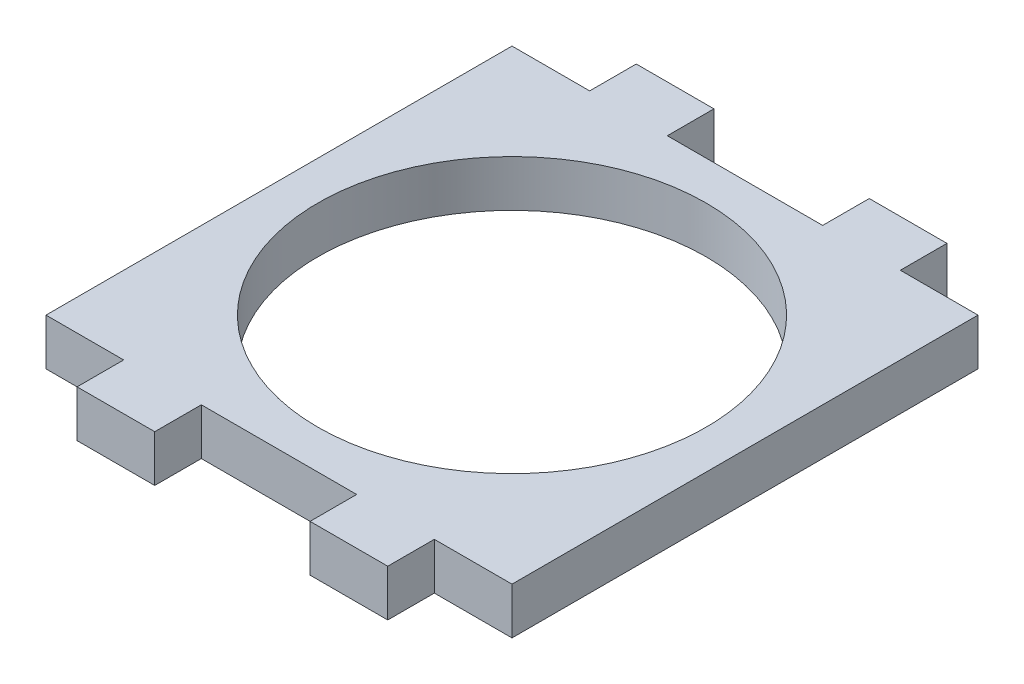
SolidWorks part; units mm, degrees
ref_plane "Front Plane" through (0, 0, 0) normal (0, 0, 1) x (1, 0, 0)
ref_plane "Top Plane" through (0, 0, 0) normal (0, 1, 0) x (1, 0, 0)
ref_plane "Right Plane" through (0, 0, 0) normal (1, 0, 0) x (0, 0, -1)
sketch "Sketch1" plane through (0, 0, 0) normal (0, 1, 0) x (1, 0, 0)
  line L0 (2.2355, 32.0745) -> (0, 30) construction
  line L1 (-30, 30) -> (30, 30)
  line L2 (-30, 30) -> (-30, -30)
  line L3 (-30, -30) -> (30, -30)
  line L4 (30, 30) -> (30, -30)
  line L5 (-30, 30) -> (30, -30) construction
  line L6 (-30, -30) -> (30, 30) construction
  line L7 (0, 30) -> (0, -30) construction
  line L8 (-30, 0) -> (30, 0) construction
  line L9 (10, -30) -> (10, -36)
  line L10 (-20, -30) -> (-10, -30)
  line L11 (-20, -30) -> (-20, -36)
  line L12 (-20, -36) -> (-10, -36)
  line L13 (-10, -30) -> (-10, -36)
  line L14 (20, -36) -> (10, -36)
  line L15 (20, -30) -> (20, -36)
  line L16 (20, -30) -> (10, -30)
  line L25 (-10, 30) -> (-10, 36)
  line L26 (20, 30) -> (10, 30)
  line L27 (20, 30) -> (20, 36)
  line L28 (20, 36) -> (10, 36)
  line L29 (10, 30) -> (10, 36)
  line L30 (-20, 36) -> (-10, 36)
  line L31 (-20, 30) -> (-20, 36)
  line L32 (-20, 30) -> (-10, 30)
  line L41 (-30, -10) -> (-36, -10) [skipped]
  line L42 (-30, 20) -> (-30, 10) [skipped]
  line L43 (-30, 20) -> (-36, 20) [skipped]
  line L44 (-36, 20) -> (-36, 10) [skipped]
  line L45 (-30, 10) -> (-36, 10) [skipped]
  line L46 (-36, -20) -> (-36, -10) [skipped]
  line L47 (-30, -20) -> (-36, -20) [skipped]
  line L48 (-30, -20) -> (-30, -10) [skipped]
  line L49 (30, 10) -> (36, 10) [skipped]
  line L50 (30, -20) -> (30, -10) [skipped]
  line L51 (30, -20) -> (36, -20) [skipped]
  line L52 (36, -20) -> (36, -10) [skipped]
  line L53 (30, -10) -> (36, -10) [skipped]
  line L54 (36, 20) -> (36, 10) [skipped]
  line L55 (30, 20) -> (36, 20) [skipped]
  line L56 (30, 20) -> (30, 10) [skipped]
  circle A0 centre (0, 0) radius 25
  point P0 (0, 0)
  point P46 (0, 0)
  dimension "D7" = 50
  dimension "D1" = 60
  dimension "D2" = 60
  dimension "D3" = 10
  dimension "D4" = 10
  dimension "D5" = 4
  dimension "D6" = 6
extrude "Boss-Extrude1" add sketch "Sketch1" along normal blind 6
